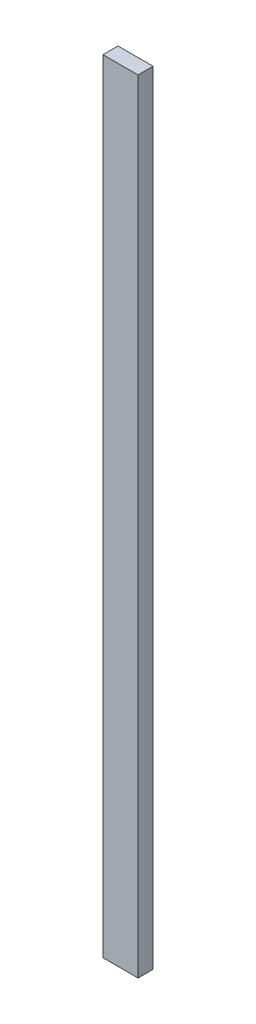
SolidWorks part; units mm, degrees
material "Pine"
ref_plane "Front Plane" through (0, 0, 0) normal (0, 0, 1) x (1, 0, 0)
ref_plane "Top Plane" through (0, 0, 0) normal (0, 1, 0) x (1, 0, 0)
ref_plane "Right Plane" through (0, 0, 0) normal (1, 0, 0) x (0, 0, -1)
sketch "Sketch2" plane through (0, 0, 0) normal (0, 1, 0) x (1, 0, 0)
  line L1 (0, 0) -> (88.9, 0)
  line L2 (0, 0) -> (0, 38.1)
  line L3 (0, 38.1) -> (88.9, 38.1)
  line L4 (88.9, 0) -> (88.9, 38.1)
  dimension "D1" = 38.1
  dimension "D2" = 88.9
extrude "Boss-Extrude1" add sketch "Sketch2" along normal blind 1981.2
